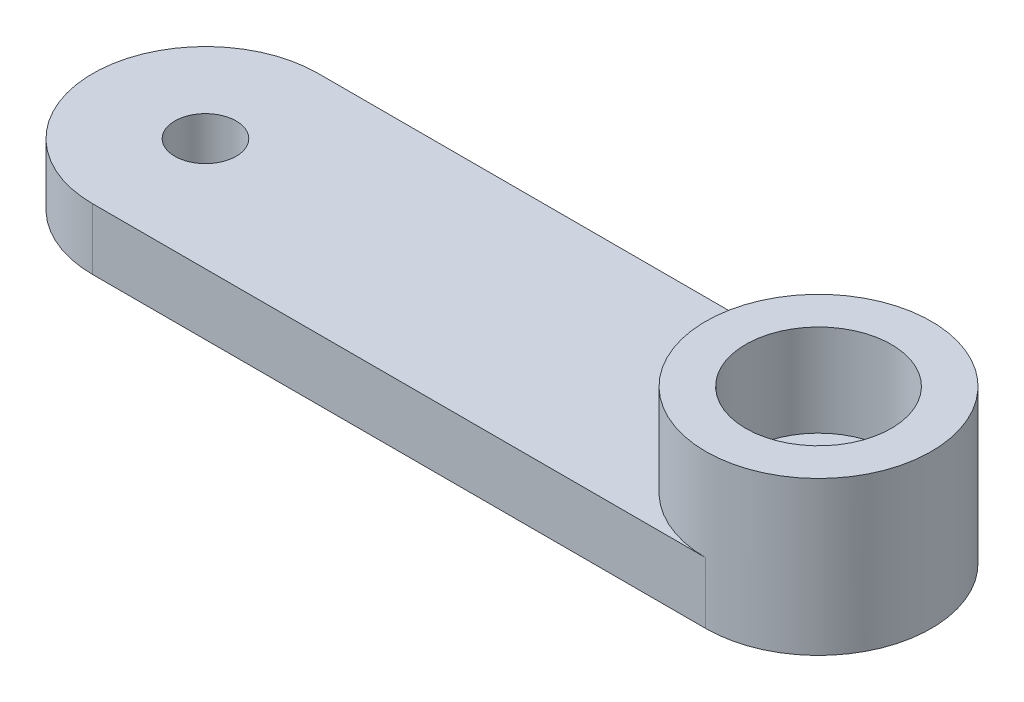
SolidWorks part; units mm, degrees
ref_plane "Front Plane" through (0, 0, 0) normal (0, 0, 1) x (1, 0, 0)
ref_plane "Top Plane" through (0, 0, 0) normal (0, 1, 0) x (1, 0, 0)
ref_plane "Right Plane" through (0, 0, 0) normal (1, 0, 0) x (0, 0, -1)
sketch "Sketch1" plane through (0, 0, 0) normal (0, 1, 0) x (1, 0, 0)
  circle A0 centre (0, 0) radius 2.435 construction
  circle A1 centre (0, 0) radius 2.565 construction
  circle A2 centre (0, 0) radius 3.68
  dimension "D1" = 4.87
  dimension "D2" = 5.13
  dimension "D3" = 7.36
extrude "Boss-Extrude1" add sketch "Sketch1" against normal blind 2 contours A2
sketch "Sketch2" plane through (0, 0, 0) normal (0, 1, 0) x (1, 0, 0)
  circle A0 centre (0, 0) radius 3.68
  circle A2 centre (0, 0) radius 2.375
  dimension "D1" = 4.75
  dimension "D3" = 7.36
extrude "Boss-Extrude2" add sketch "Sketch2" along normal blind 3
sketch "Sketch6" plane through (0, -2, 0) normal (0, -1, 0) x (1, 0, 0)
  line L0 (0, 0) -> (-20, 0) construction
  line L1 (0, -3.68) -> (-20, -3.68)
  line L2 (0, 3.68) -> (-20, 3.68)
  arc A0 (0, -3.68) -> (0, 3.68) centre (0, 0) ccw
  arc A1 (-20, 3.68) -> (-20, -3.68) centre (-20, 0) ccw
  point P3 (-10, 0)
  dimension "D1" = 3.68
  dimension "D2" = 20
extrude "Boss-Extrude3" add sketch "Sketch6" against normal blind 2
sketch "Sketch7" plane through (0, -2, 0) normal (0, -1, 0) x (1, 0, 0)
  circle A0 centre (0, 0) radius 1
  circle A1 centre (-20, 0) radius 1
  dimension "D1" = 2
  dimension "D2" = 2
extrude "Cut-Extrude4" cut sketch "Sketch7" against normal blind 2
sketch "Sketch8" plane through (0, -2, 0) normal (0, -1, 0) x (1, 0, 0)
  circle A0 centre (0, 0) radius 2
  dimension "D1" = 4
extrude "Cut-Extrude6" cut sketch "Sketch8" against normal blind 1.5
